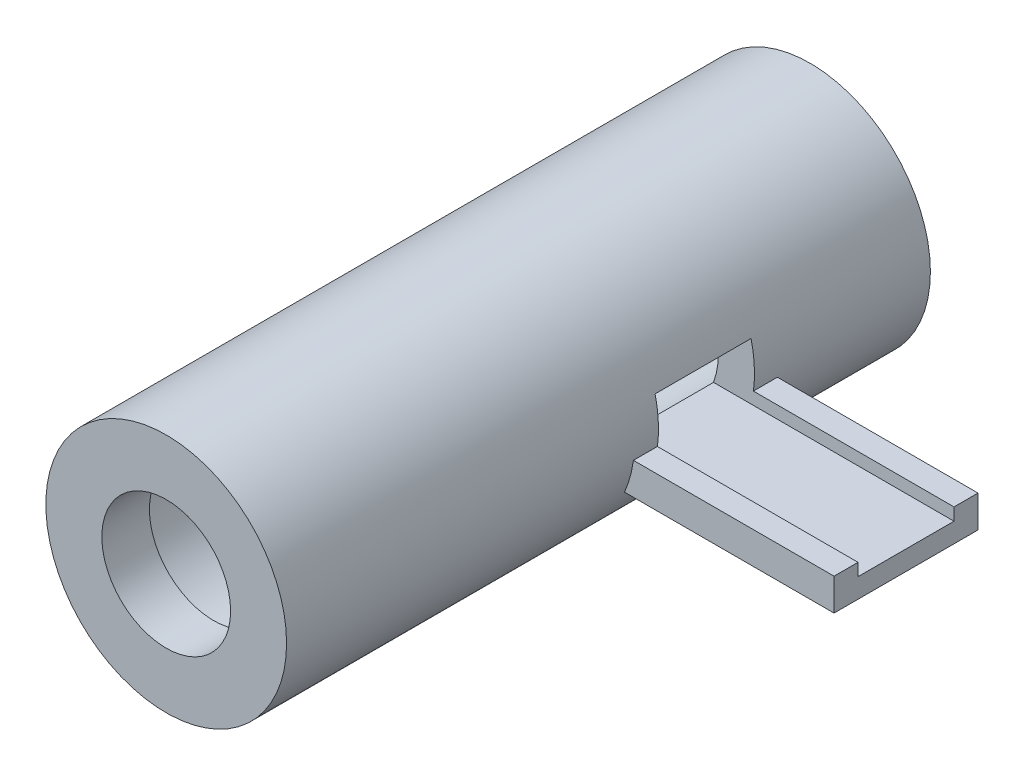
SolidWorks part; units mm, degrees
ref_plane "Front Plane" through (0, 0, 0) normal (0, 0, 1) x (1, 0, 0)
ref_plane "Top Plane" through (0, 0, 0) normal (0, 1, 0) x (1, 0, 0)
ref_plane "Right Plane" through (0, 0, 0) normal (1, 0, 0) x (0, 0, -1)
sketch "Sketch1" plane through (0, 0, 0) normal (0, 1, 0) x (1, 0, 0)
  line L0 (0, 0) -> (0, 80) construction
  line L1 (8.05, 0) -> (15.05, 0)
  line L2 (15.05, 0) -> (15.05, 80.5)
  line L3 (15.05, 80.5) -> (10.55, 80.5)
  line L4 (10.55, 80.5) -> (10.55, 5.95)
  line L5 (10.55, 5.95) -> (8.05, 5.95)
  line L6 (8.05, 5.95) -> (8.05, 0)
  dimension "D1" = 80.5
  dimension "D2" = 8.05
  dimension "D3" = 15.05
  dimension "D4" = 10.55
  dimension "D5" = 5.95
revolve "Revolve2" add sketch "Sketch1" angle 360 about L0
sketch "Sketch2" plane through (0, 0, 0) normal (1, 0, 0) x (0, 0, -1)
  line L0 (80.5, 0) -> (0, 0) construction
  line L1 (80.5, -10.55) -> (80.5, 10.55) construction
  line L2 (58.5, -3.55) -> (58.5, 3.55)
  line L3 (58.5, 3.55) -> (46.5, 3.55)
  line L4 (46.5, 3.55) -> (46.5, -3.55)
  line L5 (80.5, -15.05) -> (80.5, 15.05) construction
  line L6 (58.5, -3.55) -> (46.5, -3.55)
  line L7 (58.5, 0) -> (61.5, 0)
  line L8 (61.5, 0) -> (61.5, -7)
  line L9 (52.5, -3.55) -> (52.5, -7) construction
  line L10 (43.5, -7) -> (61.5, -7)
  line L11 (46.5, 0) -> (43.5, 0)
  line L12 (43.5, 0) -> (43.5, -7)
  point P12 (46.5, 0)
  point P13 (58.5, 0)
  dimension "D1" = 3.55
  dimension "D2" = 12
  dimension "D3" = 22
  dimension "D4" = 7
  dimension "D5" = 3
extrude "Cut-Extrude2" cut sketch "Sketch2" along normal blind 30 contours L6 L2 L3 L4
sketch "Sketch3" plane through (0, 0, 0) normal (1, 0, 0) x (0, 0, -1)
  line L0 (46.5, -2) -> (43.5, -2)
  line L1 (46.5, -3.55) -> (46.5, 3.55) construction
  line L2 (43.5, -2) -> (43.5, -6)
  line L3 (52.5, -3.55) -> (52.5, -6) construction
  line L4 (58.5, -3.55) -> (46.5, -3.55) construction
  line L5 (52.5, -6) -> (43.5, -6)
  line L6 (40.4196, 0) -> (59.1447, 0) construction
  line L7 (80.5, 0) -> (0, 0) construction
  line L8 (52.5, -6) -> (61.5, -6)
  line L9 (58.5, -2) -> (61.5, -2)
  line L10 (61.5, -2) -> (61.5, -6)
  line L11 (46.5, -2) -> (46.5, -3.55)
  line L12 (46.5, -3.55) -> (58.5, -3.55)
  line L13 (58.5, -3.55) -> (58.5, -2)
  point P9 (48, -6)
  dimension "D1" = 4
  dimension "D2" = 3
  dimension "D3" = 2
extrude "Boss-Extrude1" add sketch "Sketch3" along normal blind 40
sketch "Sketch4" plane through (0, 0, 0) normal (0, 0, 1) x (1, 0, 0)
  circle A0 centre (0, 0) radius 8.05
ref_plane "Plane1" through (0, 0, -5.95) normal (0, 0, 1) x (1, 0, 0)
sketch "Sketch5" plane through (0, 0, -5.95) normal (0, 0, 1) x (1, 0, 0)
  circle A1 centre (0, 0) radius 10.55
extrude "Cut-Extrude3" cut sketch "Sketch5" against normal through all contours A1
